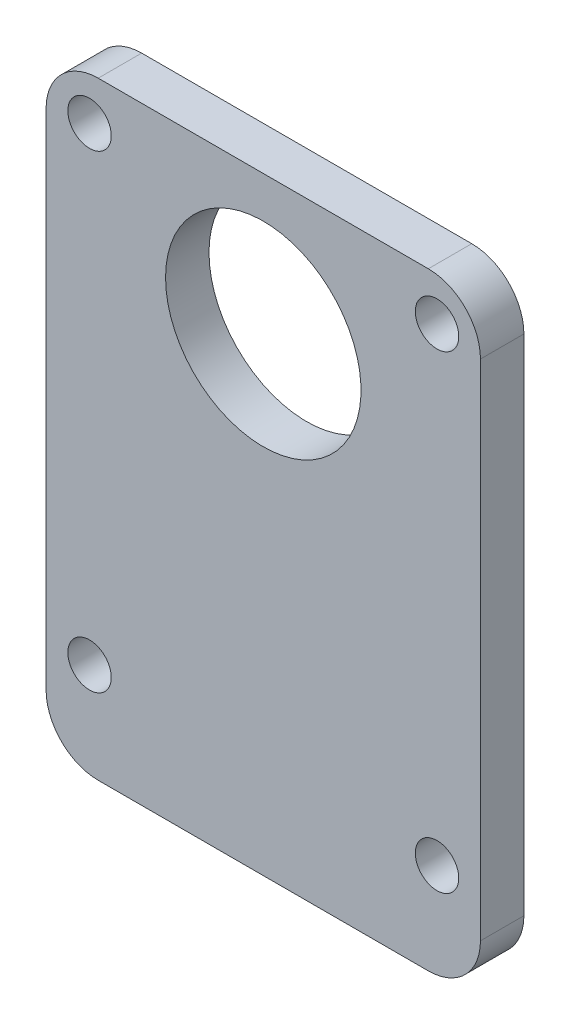
SolidWorks part; units mm, degrees
ref_plane "Front Plane" through (0, 0, 0) normal (0, 0, 1) x (1, 0, 0)
ref_plane "Top Plane" through (0, 0, 0) normal (0, 1, 0) x (1, 0, 0)
ref_plane "Right Plane" through (0, 0, 0) normal (1, 0, 0) x (0, 0, -1)
sketch "Sketch1" plane through (0, 0, 0) normal (0, 0, 1) x (1, 0, 0)
  line L0 (-19.6989, 23.2988) -> (-14.85, 29.7515)
  line L1 (-13.2512, 30.55) -> (13.2512, 30.55)
  line L2 (-20.1, 22.0973) -> (-20.1, -22.0973)
  line L3 (-13.2512, -30.55) -> (13.2512, -30.55)
  line L4 (20.1, 22.0973) -> (20.1, -22.0973)
  line L5 (-20.1, 30.55) -> (20.1, -30.55) construction
  line L6 (-20.1, -30.55) -> (20.1, 30.55) construction
  line L7 (14.85, 29.7515) -> (19.6989, 23.2988)
  line L8 (19.6989, -23.2988) -> (14.85, -29.7515)
  line L9 (-14.85, -29.7515) -> (-19.6989, -23.2988)
  arc A0 (-19.6989, -23.2988) -> (-20.1, -22.0973) centre (-18.1, -22.0973) cw
  arc A1 (-14.85, -29.7515) -> (-13.2512, -30.55) centre (-13.2512, -28.55) ccw
  arc A2 (14.85, -29.7515) -> (13.2512, -30.55) centre (13.2512, -28.55) cw
  arc A3 (19.6989, -23.2988) -> (20.1, -22.0973) centre (18.1, -22.0973) ccw
  arc A4 (19.6989, 23.2988) -> (20.1, 22.0973) centre (18.1, 22.0973) cw
  arc A5 (14.85, 29.7515) -> (13.2512, 30.55) centre (13.2512, 28.55) ccw
  arc A6 (-14.85, 29.7515) -> (-13.2512, 30.55) centre (-13.2512, 28.55) cw
  arc A7 (-19.6989, 23.2988) -> (-20.1, 22.0973) centre (-18.1, 22.0973) ccw
  point P0 (0, 0)
  point P16 (-20.1, -22.765)
  point P19 (-14.25, -30.55)
  point P22 (14.25, -30.55)
  point P25 (20.1, -22.765)
  point P28 (20.1, 22.765)
  point P31 (14.25, 30.55)
  point P34 (-14.25, 30.55)
  point P37 (-20.1, 22.765)
  dimension "D11" = 2
  dimension "D1" = 40.2
  dimension "D2" = 61.1
  dimension "D3" = 5.85
  dimension "D4" = 7.785
  dimension "D5" = 5.85
  dimension "D6" = 7.785
  dimension "D7" = 7.785
  dimension "D8" = 5.85
  dimension "D9" = 5.85
  dimension "D10" = 7.785
extrude "Boss-Extrude1" add sketch "Sketch1" against normal blind 6.35
sketch "Sketch2" plane through (0, 0, -6.35) normal (0, 0, -1) x (-1, 0, 0)
  line L0 (14.85, 29.7515) -> (14.85, -29.7515) construction
  line L1 (-14.85, 29.7515) -> (-14.85, -29.7515) construction
  line L2 (19.6989, 23.2988) -> (-19.6989, 23.2988) construction
  line L3 (20.1, -22.0973) -> (-20.1, -22.0973) construction
  line L4 (0, 30.55) -> (0, -30.55) construction
  line L5 (-13.2512, 30.55) -> (13.2512, 30.55) construction
  line L6 (13.2512, -30.55) -> (-13.2512, -30.55) construction
  circle A0 centre (17.3, 21.9488) radius 1.35
  circle A1 centre (17.3, -0.0512) radius 1.35
  circle A2 centre (17.3, -22.0512) radius 1.35
  circle A3 centre (11, -27.75) radius 1.385
  circle A4 centre (-11, -27.75) radius 1.385
  circle A5 centre (-17.3, -22.0512) radius 1.35
  circle A6 centre (-17.3, -0.0512) radius 1.35
  circle A7 centre (-17.3, 21.9488) radius 1.35
  dimension "D1" = 2.7
  dimension "D5" = 2.77
  dimension "D2" = 22
  dimension "D3" = 22
  dimension "D4" = 17.3
  dimension "D6" = 11
  dimension "D7" = 2.8
extrude "Cut-Extrude1" cut sketch "Sketch2" against normal through all
sketch "Sketch3" plane through (0, 0, -6.35) normal (0, 0, -1) x (-1, 0, 0)
  line L2 (-31.75, 38.2048) -> (31.75, 38.2048)
  line L3 (-31.75, 38.2048) -> (-31.75, -50.6952)
  line L4 (-31.75, -50.6952) -> (31.75, -50.6952)
  line L6 (31.75, 38.2048) -> (31.75, -50.6952)
  line L9 (-19.1605, 23.6188) -> (19.1605, 23.6188)
  line L10 (-19.1605, 23.6188) -> (-19.1605, -23.6188)
  line L11 (-19.1605, -23.6188) -> (19.1605, -23.6188)
  line L12 (19.1605, 23.6188) -> (19.1605, -23.6188)
  circle A0 centre (17.3, 21.9488) radius 1.35 construction
  point P0 (0, 0)
  point P6 (0, 0)
  dimension "D4" = 16.256
  dimension "D1" = 63.5
  dimension "D2" = 88.9
  dimension "D3" = 31.75
extrude "Boss-Extrude2" add sketch "Sketch3" against normal blind 6.35
sketch "Sketch5" plane through (0, 0, 0) normal (0, 0, 1) x (1, 0, 0)
  line L1 (-13.97, 30.9488) -> (13.97, 30.9488)
  line L2 (-13.97, 30.9488) -> (-13.97, -24.9312)
  line L3 (-13.97, -24.9312) -> (13.97, -24.9312)
  line L4 (13.97, 30.9488) -> (13.97, -24.9312)
  circle A0 centre (17.3, 21.9488) radius 1.35 construction
  dimension "D1" = 27.94
  dimension "D2" = 55.88
  dimension "D3" = 9
extrude "Cut-Extrude3" cut sketch "Sketch5" against normal through all
sketch "Sketch6" plane through (0, 0, -6.35) normal (0, 0, -1) x (-1, 0, 0)
  line L0 (-13.97, 30.9488) -> (13.97, 30.9488) construction
  line L1 (31.75, 38.2048) -> (-31.75, 38.2048) construction
  circle A0 centre (25.4, 31.8548) radius 3.175
  circle A1 centre (-25.4, 31.8548) radius 3.175
  circle A2 centre (-25.4, -36.7252) radius 3.175
  circle A3 centre (25.4, -36.7252) radius 3.175
  point P4 (0, 30.9488)
  dimension "D1" = 25.4
  dimension "D2" = 6.35
  dimension "D5" = 50.8
  dimension "D3" = 2
  dimension "D4" = 2
extrude "Cut-Extrude4" cut sketch "Sketch6" against normal through all
fillet "Fillet2" radius 7.62 4 edges at (-31.75, -50.6952, -3.175) (31.75, -50.6952, -3.175) (-31.75, 38.2048, -3.175) (31.75, 38.2048, -3.175)
sketch "Sketch7" plane through (0, 0, -6.35) normal (0, 0, -1) x (-1, 0, 0)
  line L1 (-20.8625, 32.0966) -> (20.8625, 32.0966)
  line L2 (-20.8625, 32.0966) -> (-20.8625, -25.7617)
  line L3 (-20.8625, -25.7617) -> (20.8625, -25.7617)
  line L4 (20.8625, 32.0966) -> (20.8625, -25.7617)
  line L5 (-20.8625, 32.0966) -> (20.8625, -25.7617) construction
  line L6 (-20.8625, -25.7617) -> (20.8625, 32.0966) construction
  point P0 (0, 3.1674)
extrude "Boss-Extrude3" add sketch "Sketch7" against normal blind 6.35
sketch "Sketch8" plane through (0, 0, -6.35) normal (0, 0, -1) x (-1, 0, 0)
  line L0 (24.13, 38.2048) -> (-24.13, 38.2048) construction
  circle A0 centre (0, 17.8848) radius 14.2875
  dimension "D1" = 20.32
extrude "Cut-Extrude5" cut sketch "Sketch8" against normal blind 6.35
